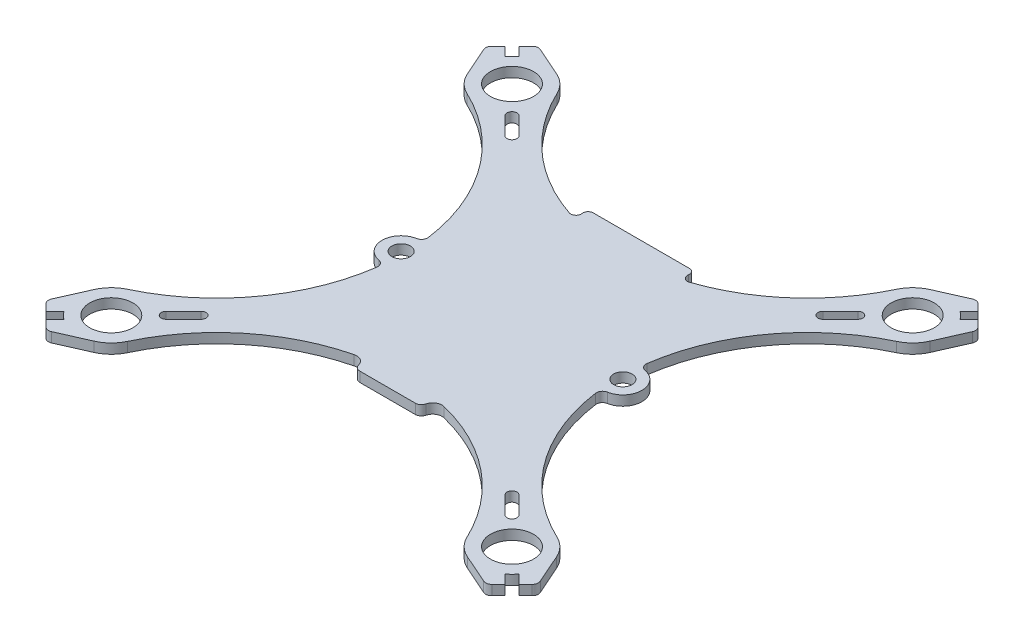
SolidWorks part; units mm, degrees
ref_plane "前视基准面" through (0, 0, 0) normal (0, 0, 1) x (1, 0, 0)
ref_plane "上视基准面" through (0, 0, 0) normal (0, 1, 0) x (1, 0, 0)
ref_plane "右视基准面" through (0, 0, 0) normal (1, 0, 0) x (0, 0, -1)
sketch "草图1" plane through (0, 0, 0) normal (0, 1, 0) x (1, 0, 0)
  line L1 (-40.4758, 115.29) -> (366.6, 118.5757) construction
  line L2 (23.2235, -0.0262) -> (88.2774, 65.0276) construction
  line L4 (23.2235, 65.0276) -> (88.2774, 65.0276)
  line L5 (23.2235, 65.0276) -> (23.2235, -0.0262)
  line L6 (23.2235, -0.0262) -> (88.2774, -0.0262)
  line L7 (88.2774, 65.0276) -> (88.2774, -0.0262)
  line L8 (88.2774, -0.0262) -> (7.794, 80.4571) construction
  line L9 (55.7505, 76.7873) -> (55.7505, -19.2538) construction
  line L10 (2.9505, 32.5007) -> (108.2303, 32.5007) construction
  line L11 (47.9505, 53.5007) -> (63.5505, 53.5007)
  line L12 (51.2505, 12.3007) -> (60.2505, 12.3007)
  line L13 (27.6783, 4.4285) -> (30.5067, 7.257) construction
  line L14 (27.1126, 4.9942) -> (29.9411, 7.8227)
  line L15 (28.244, 3.8629) -> (31.0724, 6.6913)
  line L16 (27.6783, 60.5728) -> (30.5067, 57.7444) construction
  line L17 (28.244, 61.1385) -> (31.0724, 58.3101)
  line L18 (27.1126, 60.0071) -> (29.9411, 57.1787)
  line L19 (83.8226, 60.5728) -> (80.9942, 57.7444) construction
  line L20 (84.3883, 60.0071) -> (81.5599, 57.1787)
  line L21 (83.2569, 61.1385) -> (80.4285, 58.3101)
  line L22 (83.8226, 4.4285) -> (80.9942, 7.257) construction
  line L23 (83.2569, 3.8629) -> (80.4285, 6.6913)
  line L24 (84.3883, 4.9942) -> (81.5599, 7.8227)
  line L25 (18.8101, 68.3096) -> (17.3546, 69.7652)
  line L26 (19.9415, 69.441) -> (18.4859, 70.8966)
  line L27 (16.2839, 68.6945) -> (17.3546, 69.7652)
  line L28 (16.0767, 67.5825) -> (18.1947, 62.8003)
  line L29 (20.6687, 72.1745) -> (25.4508, 70.0564)
  line L30 (18.4859, 70.8966) -> (19.5566, 71.9672)
  line L31 (95.4242, 67.5825) -> (93.3062, 62.8003)
  line L32 (95.217, 68.6945) -> (94.1464, 69.7652)
  line L33 (92.6908, 68.3096) -> (94.1464, 69.7652)
  line L34 (93.015, 70.8966) -> (91.9443, 71.9672)
  line L35 (91.5594, 69.441) -> (93.015, 70.8966)
  line L36 (90.8323, 72.1745) -> (86.0501, 70.0564)
  line L37 (95.4242, -2.5811) -> (93.3062, 2.2011)
  line L38 (95.217, -3.6932) -> (94.1464, -4.7638)
  line L39 (92.6908, -3.3083) -> (94.1464, -4.7638)
  line L40 (91.5594, -4.4396) -> (93.015, -5.8952)
  line L41 (93.015, -5.8952) -> (91.9443, -6.9659)
  line L42 (90.8323, -7.1731) -> (86.0501, -5.0551)
  line L43 (20.6687, -7.1731) -> (25.4508, -5.0551)
  line L44 (18.4859, -5.8952) -> (19.5566, -6.9659)
  line L45 (19.9415, -4.4396) -> (18.4859, -5.8952)
  line L46 (18.8101, -3.3083) -> (17.3546, -4.7638)
  line L47 (16.2839, -3.6932) -> (17.3546, -4.7638)
  line L48 (16.0767, -2.5811) -> (18.1947, 2.2011)
  circle A0 centre (23.2235, -0.0262) radius 22.5
  circle A1 centre (23.2235, 65.0276) radius 22.5
  circle A2 centre (88.2774, 65.0276) radius 22.5
  circle A3 centre (88.2774, -0.0262) radius 22.5
  arc A4 (20.8666, 4.9432) -> (18.1947, 2.2011) centre (23.2235, -0.0262) ccw
  circle A5 centre (23.2235, -0.0262) radius 3.5
  arc A6 (28.1929, 67.3845) -> (25.4508, 70.0564) centre (23.2235, 65.0276) ccw
  circle A7 centre (23.2235, 65.0276) radius 3.5
  arc A8 (90.6343, 60.0582) -> (93.3062, 62.8003) centre (88.2774, 65.0276) ccw
  circle A9 centre (88.2774, 65.0276) radius 3.5
  arc A10 (83.308, -2.3832) -> (86.0501, -5.0551) centre (88.2774, -0.0262) ccw
  circle A11 centre (88.2774, -0.0262) radius 3.5
  arc A12 (20.8666, 4.9432) -> (38.0097, 28.3297) centre (7.7963, 32.5007) ccw
  arc A13 (90.6343, 4.9432) -> (73.4912, 28.3297) centre (103.7046, 32.5007) cw
  arc A14 (28.1929, -2.3832) -> (48.4637, 14.1633) centre (55.7505, -15.4535) cw
  arc A15 (28.1929, 67.3845) -> (46.004, 51.554) centre (55.7505, 80.4548) ccw
  circle A16 centre (37.7505, 32.5007) radius 1.5
  arc A17 (37.1975, 35.551) -> (37.1975, 29.4504) centre (37.7505, 32.5007) ccw
  circle A18 centre (73.7505, 32.5007) radius 1.5
  arc A19 (74.3034, 35.551) -> (74.3034, 29.4504) centre (73.7505, 32.5007) cw
  arc A20 (38.0097, 36.6717) -> (37.1975, 35.551) centre (37.0191, 36.5349) cw
  arc A21 (38.0097, 36.6717) -> (20.8666, 60.0582) centre (7.7963, 32.5007) ccw
  arc A22 (37.1975, 29.4504) -> (38.0097, 28.3297) centre (37.0191, 28.4664) cw
  arc A23 (73.4912, 36.6717) -> (90.6343, 60.0582) centre (103.7046, 32.5007) cw
  arc A24 (73.4912, 36.6717) -> (74.3034, 35.551) centre (74.4818, 36.5349) ccw
  arc A25 (74.3034, 29.4504) -> (73.4912, 28.3297) centre (74.4818, 28.4664) ccw
  arc A26 (64.3879, 52.5051) -> (63.5505, 53.5007) centre (63.5505, 52.6507) ccw
  arc A27 (64.3879, 52.5051) -> (65.497, 51.554) centre (65.2253, 52.3595) ccw
  arc A28 (47.113, 52.5051) -> (47.9505, 53.5007) centre (47.9505, 52.6507) cw
  arc A29 (47.113, 52.5051) -> (46.004, 51.554) centre (46.2756, 52.3595) cw
  arc A30 (65.497, 51.554) -> (83.308, 67.3845) centre (55.7505, 80.4548) ccw
  arc A31 (60.2505, 12.3007) -> (61.2218, 13.0631) centre (60.2505, 13.3007) ccw
  arc A32 (63.0372, 14.1633) -> (61.2218, 13.0631) centre (62.6789, 12.7067) ccw
  arc A33 (51.2505, 12.3007) -> (50.2791, 13.0631) centre (51.2505, 13.3007) cw
  arc A34 (48.4637, 14.1633) -> (50.2791, 13.0631) centre (48.822, 12.7067) cw
  arc A35 (63.0372, 14.1633) -> (83.308, -2.3832) centre (55.7505, -15.4535) cw
  arc A36 (27.1126, 4.9942) -> (28.244, 3.8629) centre (27.6783, 4.4285) ccw
  arc A37 (31.0724, 6.6913) -> (29.9411, 7.8227) centre (30.5067, 7.257) ccw
  arc A38 (28.244, 61.1385) -> (27.1126, 60.0071) centre (27.6783, 60.5728) ccw
  arc A39 (29.9411, 57.1787) -> (31.0724, 58.3101) centre (30.5067, 57.7444) ccw
  arc A40 (84.3883, 60.0071) -> (83.2569, 61.1385) centre (83.8226, 60.5728) ccw
  arc A41 (80.4285, 58.3101) -> (81.5599, 57.1787) centre (80.9942, 57.7444) ccw
  arc A42 (83.2569, 3.8629) -> (84.3883, 4.9942) centre (83.8226, 4.4285) ccw
  arc A43 (81.5599, 7.8227) -> (80.4285, 6.6913) centre (80.9942, 7.257) ccw
  arc A44 (19.5566, 71.9672) -> (20.6687, 72.1745) centre (20.2637, 71.2601) cw
  arc A45 (16.2839, 68.6945) -> (16.0767, 67.5825) centre (16.991, 67.9874) ccw
  arc A46 (95.217, 68.6945) -> (95.4242, 67.5825) centre (94.5099, 67.9874) cw
  arc A47 (91.9443, 71.9672) -> (90.8323, 72.1745) centre (91.2372, 71.2601) ccw
  arc A48 (18.1947, 62.8003) -> (20.8666, 60.0582) centre (23.2235, 65.0276) ccw
  arc A49 (19.9415, 69.441) -> (18.8101, 68.3096) centre (23.2235, 65.0276) ccw
  arc A50 (86.0501, 70.0564) -> (83.308, 67.3845) centre (88.2774, 65.0276) ccw
  arc A51 (92.6908, 68.3096) -> (91.5594, 69.441) centre (88.2774, 65.0276) ccw
  arc A52 (95.217, -3.6932) -> (95.4242, -2.5811) centre (94.5099, -2.9861) ccw
  arc A53 (91.9443, -6.9659) -> (90.8323, -7.1731) centre (91.2372, -6.2588) cw
  arc A54 (19.5566, -6.9659) -> (20.6687, -7.1731) centre (20.2637, -6.2588) ccw
  arc A55 (16.2839, -3.6932) -> (16.0767, -2.5811) centre (16.991, -2.9861) cw
  arc A56 (18.8101, -3.3083) -> (19.9415, -4.4396) centre (23.2235, -0.0262) ccw
  arc A57 (25.4508, -5.0551) -> (28.1929, -2.3832) centre (23.2235, -0.0262) ccw
  arc A58 (93.3062, 2.2011) -> (90.6343, 4.9432) centre (88.2774, -0.0262) ccw
  arc A59 (91.5594, -4.4396) -> (92.6908, -3.3083) centre (88.2774, -0.0262) ccw
  point P7 (55.7505, 32.5007)
  point P16 (9.124, 69.0573)
  point P21 (55.7505, 32.5007)
  point P33 (55.7505, 32.5007)
  point P53 (38.1409, 35.576)
  point P59 (73.3601, 35.576)
  point P66 (55.7505, 53.5007)
  point P68 (72.5245, 69.0573)
  point P80 (55.7505, 12.3007)
  point P87 (29.0925, 5.8428)
  point P96 (29.0925, 59.1586)
  point P103 (82.4084, 59.1586)
  point P110 (82.4084, 5.8428)
  point P115 (55.7505, 32.5007)
  point P116 (72.5245, 5.6569)
  point P122 (20.0416, 72.4522)
  point P125 (15.7989, 68.2096)
  dimension "D1" = 92
  dimension "D5" = 7
  dimension "D6" = 5.5
  dimension "D7" = 30.5
  dimension "D8" = 30.5
  dimension "D10" = 3
  dimension "D11" = 18
  dimension "D12" = 1
  dimension "D13" = 1
  dimension "D14" = 21
  dimension "D15" = 1.7
  dimension "D16" = 1.7
  dimension "D17" = 7.8
  dimension "D18" = 20.2
  dimension "D19" = 3
  dimension "D20" = 2
  dimension "D4" = 11
  dimension "D22" = 1.6
  dimension "D23" = 4
  dimension "D24" = 7
  dimension "D21" = 4.5
  dimension "D28" = 7
  dimension "D29" = 0.8
  dimension "D9" = 6.2
  dimension "D3" = 4
  dimension "D26" = 7
  dimension "D27" = 5.5
  dimension "D2" = 45
  dimension "D25" = 5.5
  dimension "D32" = 1
  dimension "D33" = 5.5
  dimension "D30" = 7.5
  dimension "D31" = 3
  dimension "D34" = 4
extrude "凸台-拉伸1" add sketch "草图1" along normal blind 1.6 contours A13 A25 A19 A24 A23 A8 L31 A46 L32 L33 A51 L35 L34 A47 L36 A50 A30 A27 A26 L11 A28 A29 A15 A6 L29 A44 L30 L26 A49 L25 L27 A45 L28 A48 A21 A20 A17 A22 A12 A4 L48 A55 L47 L46 A56 L45 L44 A54 L43 A57 A14 A34 A33 L12 A31 A32 A35 A10 L42 A53 L41 L40 A59 L39 L38 A52 L37 A58
sketch "草图2" plane through (0, 0, 0) normal (0, 1, 0) x (1, 0, 0)
  line L0 (84.3883, 4.9942) -> (81.5599, 7.8227) construction
  line L1 (83.2569, 3.8629) -> (80.4285, 6.6913) construction
  line L2 (84.3883, 4.9942) -> (81.5599, 7.8227)
  line L3 (84.3883, 60.0071) -> (81.5599, 57.1787) construction
  line L4 (83.2569, 61.1385) -> (80.4285, 58.3101) construction
  line L5 (83.2569, 3.8629) -> (80.4285, 6.6913)
  line L6 (27.1126, 60.0071) -> (29.9411, 57.1787) construction
  line L7 (28.244, 61.1385) -> (31.0724, 58.3101) construction
  line L8 (27.1126, 4.9942) -> (29.9411, 7.8227) construction
  line L9 (28.244, 3.8629) -> (31.0724, 6.6913) construction
  line L10 (27.1126, 60.0071) -> (29.9411, 57.1787)
  line L11 (28.244, 61.1385) -> (31.0724, 58.3101)
  line L12 (27.1126, 4.9942) -> (29.9411, 7.8227)
  line L13 (28.244, 3.8629) -> (31.0724, 6.6913)
  line L14 (84.3883, 60.0071) -> (81.5599, 57.1787)
  line L15 (83.2569, 61.1385) -> (80.4285, 58.3101)
  circle A0 centre (88.2774, -0.0262) radius 3.5 construction
  circle A1 centre (88.2774, -0.0262) radius 3.5
  circle A2 centre (88.2774, 65.0276) radius 3.5 construction
  circle A3 centre (88.2774, 65.0276) radius 3.5
  arc A4 (83.2569, 3.8629) -> (84.3883, 4.9942) centre (83.8226, 4.4285) ccw construction
  arc A5 (83.2569, 3.8629) -> (84.3883, 4.9942) centre (83.8226, 4.4285) ccw
  arc A6 (80.4285, 58.3101) -> (81.5599, 57.1787) centre (80.9942, 57.7444) ccw construction
  arc A7 (84.3883, 60.0071) -> (83.2569, 61.1385) centre (83.8226, 60.5728) ccw construction
  arc A8 (81.5599, 7.8227) -> (80.4285, 6.6913) centre (80.9942, 7.257) ccw construction
  arc A9 (81.5599, 7.8227) -> (80.4285, 6.6913) centre (80.9942, 7.257) ccw
  arc A10 (27.1126, 4.9942) -> (28.244, 3.8629) centre (27.6783, 4.4285) ccw construction
  circle A11 centre (23.2235, -0.0262) radius 3.5 construction
  circle A12 centre (23.2235, 65.0276) radius 3.5 construction
  circle A13 centre (37.7505, 32.5007) radius 1.5 construction
  arc A14 (27.1126, 4.9942) -> (28.244, 3.8629) centre (27.6783, 4.4285) ccw
  circle A15 centre (23.2235, -0.0262) radius 3.5
  circle A16 centre (23.2235, 65.0276) radius 3.5
  circle A17 centre (37.7505, 32.5007) radius 1.5
  arc A18 (29.9411, 57.1787) -> (31.0724, 58.3101) centre (30.5067, 57.7444) ccw construction
  arc A19 (28.244, 61.1385) -> (27.1126, 60.0071) centre (27.6783, 60.5728) ccw construction
  arc A20 (31.0724, 6.6913) -> (29.9411, 7.8227) centre (30.5067, 7.257) ccw construction
  circle A21 centre (73.7505, 32.5007) radius 1.5 construction
  arc A22 (29.9411, 57.1787) -> (31.0724, 58.3101) centre (30.5067, 57.7444) ccw
  arc A23 (28.244, 61.1385) -> (27.1126, 60.0071) centre (27.6783, 60.5728) ccw
  arc A24 (31.0724, 6.6913) -> (29.9411, 7.8227) centre (30.5067, 7.257) ccw
  circle A25 centre (73.7505, 32.5007) radius 1.5
  arc A26 (80.4285, 58.3101) -> (81.5599, 57.1787) centre (80.9942, 57.7444) ccw
  arc A27 (84.3883, 60.0071) -> (83.2569, 61.1385) centre (83.8226, 60.5728) ccw
extrude "切除-拉伸2" cut sketch "草图2" along normal through all
sketch "草图3" plane through (0, 1.6, 0) normal (0, 1, 0) x (1, 0, 0)
  line L0 (23.2235, -0.0262) -> (88.2774, 65.0276) construction
  line L1 (23.2235, 65.0276) -> (88.2774, -0.0262) construction
  line L2 (10.7505, 77.5007) -> (100.7505, 77.5007)
  line L3 (5.7505, -17.4993) -> (105.7505, -17.4993)
  line L4 (5.7505, -17.4993) -> (5.7505, 82.5007)
  line L5 (5.7505, 82.5007) -> (105.7505, 82.5007)
  line L6 (105.7505, -17.4993) -> (105.7505, 82.5007)
  line L7 (5.7505, -17.4993) -> (105.7505, 82.5007) construction
  line L8 (5.7505, 82.5007) -> (105.7505, -17.4993) construction
  line L9 (100.7505, -12.4993) -> (100.7505, 77.5007)
  line L10 (10.7505, -12.4993) -> (100.7505, -12.4993)
  line L11 (10.7505, -12.4993) -> (10.7505, 77.5007)
  point P8 (55.7505, 32.5007)
  point P9 (55.7505, 32.5007)
  dimension "D1" = 100
  dimension "D2" = 100
  dimension "D3" = 5
